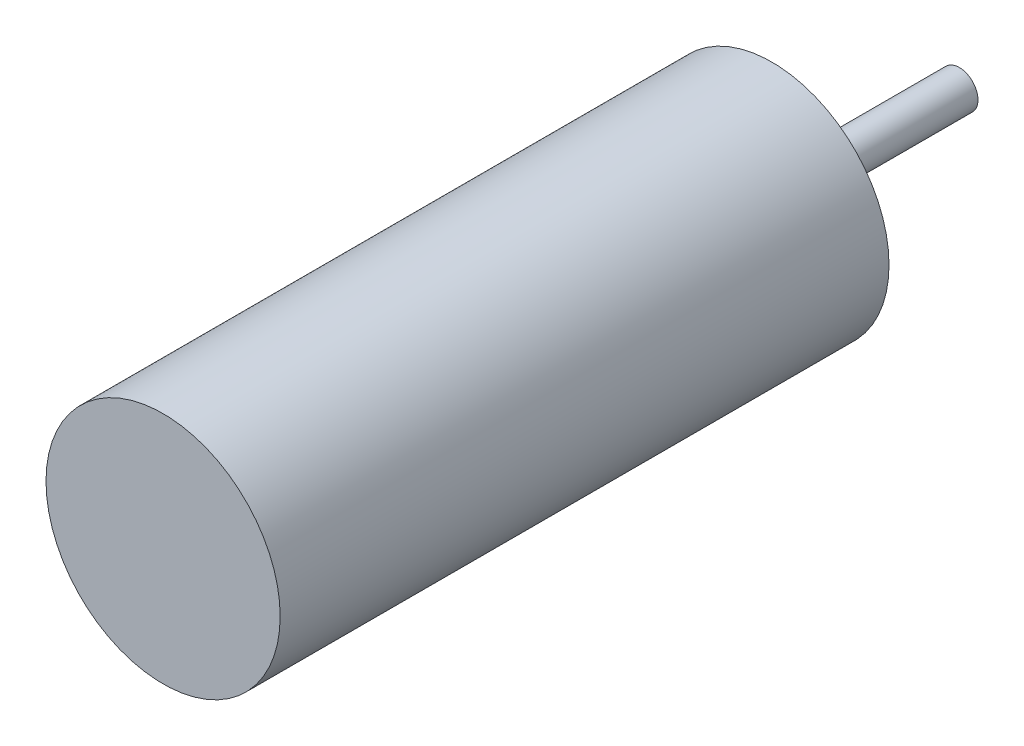
SolidWorks part; units mm, degrees
ref_plane "前视基准面" through (0, 0, 0) normal (0, 0, 1) x (1, 0, 0)
ref_plane "上视基准面" through (0, 0, 0) normal (0, 1, 0) x (1, 0, 0)
ref_plane "右视基准面" through (0, 0, 0) normal (1, 0, 0) x (0, 0, -1)
sketch "草图1" plane through (0, 0, 0) normal (0, 0, 1) x (1, 0, 0)
  circle A0 centre (0, 0) radius 2
  dimension "D1" = 4
extrude "凸台-拉伸1" add sketch "草图1" along normal blind 20
sketch "草图2" plane through (0, 0, 20) normal (0, 0, 1) x (1, 0, 0)
  circle A0 centre (0, 0) radius 12.5
  dimension "D1" = 25
extrude "凸台-拉伸2" add sketch "草图2" along normal blind 65
